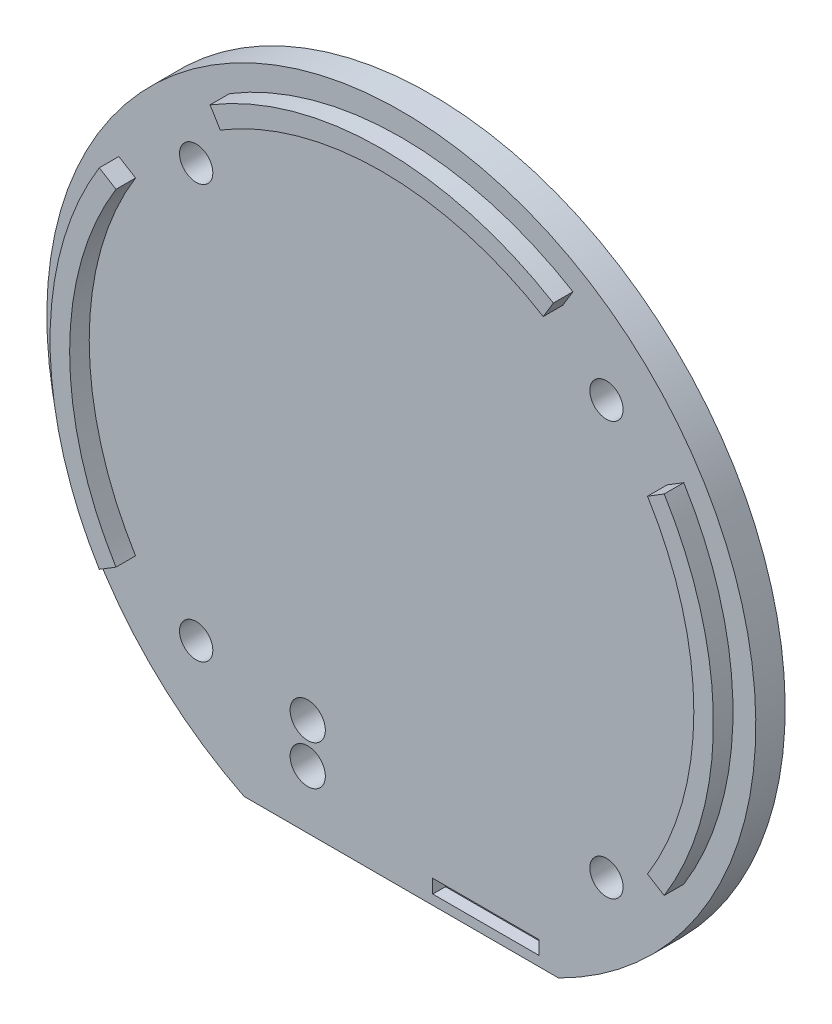
SolidWorks part; units mm, degrees
ref_plane "Front" through (0, 0, 0) normal (0, 0, 1) x (1, 0, 0)
ref_plane "Top" through (0, 0, 0) normal (0, 1, 0) x (1, 0, 0)
ref_plane "Right" through (0, 0, 0) normal (1, 0, 0) x (0, 0, -1)
sketch "Sketch1" plane through (0, 0, 0) normal (0, 0, 1) x (1, 0, 0)
  line L2 (36.21, 0) -> (-36.21, 0) construction
  line L3 (-16.06, -32.4537) -> (16.06, -32.4537)
  arc A1 (16.06, -32.4537) -> (-16.06, -32.4537) centre (0, 0) ccw
  point P6 (0, 0)
  dimension "D1" = 36.21
  dimension "D3" = 32.12
extrude "Boss-Extrude1" add sketch "Sketch1" along normal blind 3 contours A1 L3
sketch "Sketch2" plane through (0, 0, 3) normal (0, 0, 1) x (1, 0, 0)
  line L0 (0, 36.21) -> (0, 0) construction
  line L1 (-20.955, 21.12) -> (20.955, 21.12) construction
  line L2 (-36.21, 0) -> (36.21, 0) construction
  line L3 (-20.955, 21.12) -> (-20.955, -21.12) construction
  arc A0 (16.06, -32.4537) -> (-16.06, -32.4537) centre (0, 0) ccw construction
  circle A1 centre (-20.955, 21.12) radius 1.7
  circle A2 centre (20.955, 21.12) radius 1.7
  circle A5 centre (-20.955, -21.12) radius 1.7
  circle A6 centre (20.955, -21.12) radius 1.7
  point P8 (0, 21.12)
  dimension "D3" = 3.4
  dimension "D1" = 15.09
  dimension "D2" = 41.91
  dimension "D4" = 42.24
extrude "Cut-Extrude1" cut sketch "Sketch2" against normal up to surface (3 mm away) up to face at (0, 1.8782, 0)
sketch "Sketch4" plane through (0, 0, 3) normal (0, 0, 1) x (1, 0, 0)
  line L1 (0, 36.21) -> (0, -32.4537) construction
  line L2 (-17.5341, 28.9898) -> (-16.4991, 27.2785)
  line L4 (-28.8514, 17.761) -> (-27.1482, 16.7125)
  line L5 (-28.8514, -17.761) -> (-27.1482, -16.7125)
  line L7 (-16.06, -32.4537) -> (16.06, -32.4537) construction
  line L8 (17.5341, 28.9898) -> (16.4991, 27.2785)
  line L9 (-36.21, 0) -> (36.21, 0) construction
  line L10 (28.8514, 17.761) -> (27.1482, 16.7125)
  line L11 (28.8514, -17.761) -> (27.1482, -16.7125)
  arc A0 (-28.8514, 17.761) -> (-28.8514, -17.761) centre (0, 0) ccw
  arc A1 (16.06, -32.4537) -> (-16.06, -32.4537) centre (0, 0) ccw construction
  arc A2 (-27.1482, 16.7125) -> (-27.1482, -16.7125) centre (0, 0) ccw
  arc A3 (16.4991, 27.2785) -> (-16.4991, 27.2785) centre (0, 0) ccw
  arc A4 (16.06, -32.4537) -> (-16.06, -32.4537) centre (0, 0) ccw construction
  arc A5 (17.5341, 28.9898) -> (-17.5341, 28.9898) centre (0, 0) ccw
  circle A6 centre (-20.955, 21.12) radius 1.7 construction
  circle A7 centre (20.955, 21.12) radius 1.7 construction
  arc A8 (28.8514, 17.761) -> (28.8514, -17.761) centre (0, 0) cw
  arc A9 (27.1482, 16.7125) -> (27.1482, -16.7125) centre (0, 0) cw
  point P13 (0, 33.88)
  point P16 (-33.88, 0)
  point P29 (0, 36.21)
  dimension "D2" = 2.33
  dimension "D3" = 2
  dimension "D4" = 7
  dimension "D5" = 7
  dimension "D1" = 2
extrude "Boss-Extrude2" add sketch "Sketch4" along normal blind 2
sketch "Sketch6" plane through (0, 0, 0) normal (0, 0, -1) x (-1, 0, 0)
  line L0 (9.56, -32.4537) -> (9.56, -22.4537) construction
  line L1 (16.06, -32.4537) -> (-16.06, -32.4537) construction
  circle A0 centre (9.56, -22.4537) radius 1.8
  circle A1 centre (9.56, -26.5237) radius 1.8
  dimension "D3" = 3.6
  dimension "D1" = 10
  dimension "D2" = 6.5
  dimension "D4" = 4.07
extrude "Cut-Extrude2" cut sketch "Sketch6" against normal up to surface (3 mm away) up to face at (19.255, 21.12, 3)
sketch "Sketch8" plane through (0, 0, 3) normal (0, 0, 1) x (1, 0, 0)
  line L0 (-16.06, -32.4537) -> (16.06, -32.4537) construction
  line L1 (3.21, -31.4537) -> (14.06, -31.4537)
  line L2 (3.21, -31.4537) -> (3.21, -30.0537)
  line L3 (3.21, -30.0537) -> (14.06, -30.0537)
  line L4 (14.06, -31.4537) -> (14.06, -30.0537)
  line L5 (16.06, -32.4537) -> (16.06, -24.7151) construction
  dimension "D1" = 1
  dimension "D2" = 10.85
  dimension "D3" = 1.4
  dimension "D4" = 2
extrude "Cut-Extrude4" cut sketch "Sketch8" against normal blind 1.3
